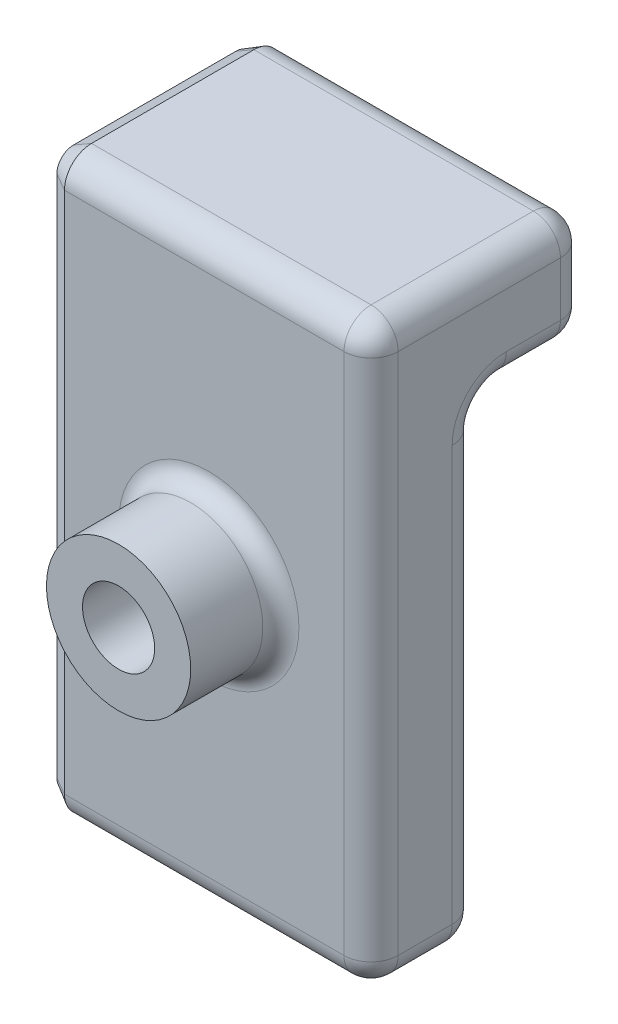
SolidWorks part; units mm, degrees
ref_plane "Front Plane" through (0, 0, 0) normal (0, 0, 1) x (1, 0, 0)
ref_plane "Top Plane" through (0, 0, 0) normal (0, 1, 0) x (1, 0, 0)
ref_plane "Right Plane" through (0, 0, 0) normal (1, 0, 0) x (0, 0, -1)
sketch "Sketch2" plane through (0, 0, 0) normal (1, 0, 0) x (0, 0, -1)
  line L0 (0, 0) -> (0, 32)
  line L1 (0, 32) -> (12, 32)
  line L2 (12, 32) -> (12, 26)
  line L3 (12, 26) -> (6, 26)
  line L4 (6, 26) -> (6, 0)
  line L5 (6, 0) -> (0, 0)
  dimension "D1" = 32
  dimension "D2" = 6
  dimension "D3" = 6
  dimension "D4" = 6
extrude "Boss-Extrude1" add sketch "Sketch2" along normal blind 18
sketch "Sketch3" plane through (0, 0, 0) normal (0, 0, 1) x (1, 0, 0)
  line L0 (18, 32) -> (18, 0) construction
  line L1 (18, 32) -> (0, 32) construction
  circle A0 centre (9, 16) radius 2
  point P4 (18, 16)
  point P8 (9, 32)
  dimension "D1" = 4
extrude "Cut-Extrude1" cut sketch "Sketch3" against normal blind 18
fillet "Fillet1" radius 1.5 12 edges at (18, 13, -6) (9, 26, -12) (9, 32, -12) (18, 26, -9) (18, 32, -6) (18, 29, -12) (9, 26, -6) (18, 16, 0) (9, 32, 0) (18, 0, -3) (9, 0, -6) (9, 0, 0)
chamfer "Chamfer1" distance 1 angle 30 12 edges at (0, 16, 0) (0, 13, -6) (0, 25.5607, -6.4393) (0, 26, -9) (0, 26.4393, -11.5607) (0, 29, -12) (0, 31.5607, -11.5607) (0, 0, -3) (0, 32, -6) (0, 0.4393, -5.5607) (0, 31.5607, -0.4393) (0, 0.4393, -0.4393)
sketch "Sketch4" plane through (0, 0, 0) normal (0, 0, 1) x (1, 0, 0)
  circle A0 centre (9, 16) radius 4
  circle A1 centre (9, 16) radius 2 construction
  circle A2 centre (9, 16) radius 2
  dimension "D1" = 8
extrude "Boss-Extrude2" add sketch "Sketch4" along normal blind 5
fillet "Fillet3" radius 1 1 edges at (5, 16, 0)
